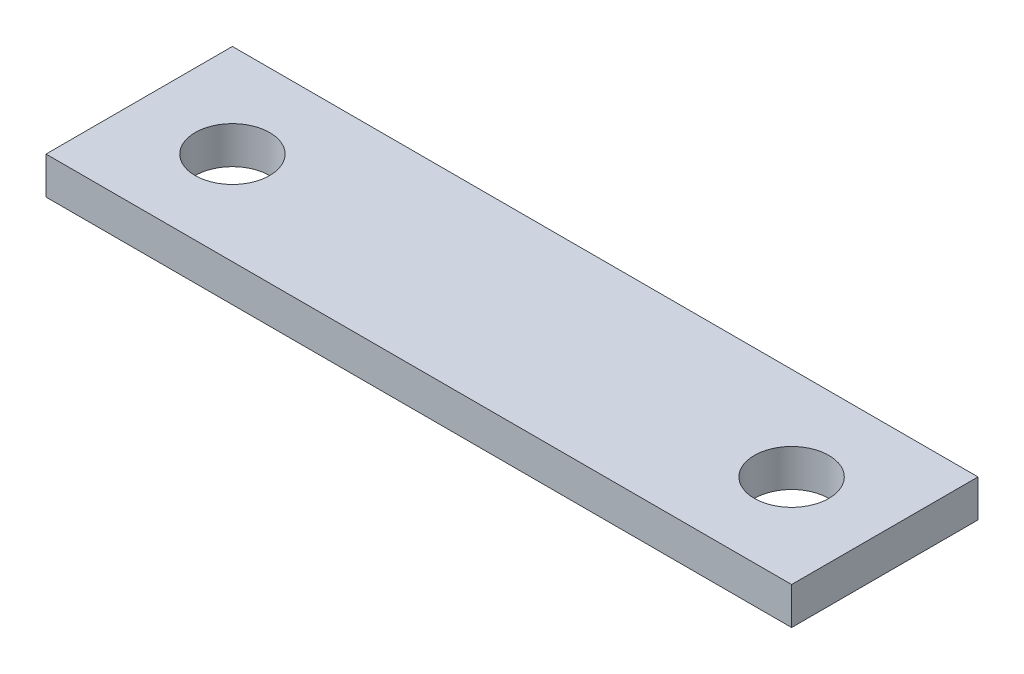
SolidWorks part; units mm, degrees
ref_plane "前视基准面" through (0, 0, 0) normal (0, 0, 1) x (1, 0, 0)
ref_plane "上视基准面" through (0, 0, 0) normal (0, 1, 0) x (1, 0, 0)
ref_plane "右视基准面" through (0, 0, 0) normal (1, 0, 0) x (0, 0, -1)
sketch "草图1" plane through (0, 0, 0) normal (0, 1, 0) x (1, 0, 0)
  line L0 (-1000, 15) -> (49000, 15) construction
  line L1 (0, 0) -> (120, 0)
  line L2 (0, 0) -> (0, 30)
  line L3 (0, 30) -> (120, 30)
  line L4 (120, 0) -> (120, 30)
  line L5 (60, -1000) -> (60, 49000) construction
  circle A0 centre (15, 15) radius 6
  circle A1 centre (105, 15) radius 6
  point P8 (0, 15)
  point P15 (60, 0)
  dimension "D3" = 12
  dimension "D4" = 12
  dimension "D1" = 120
  dimension "D2" = 30
  dimension "D5" = 90
extrude "凸台-拉伸1" add sketch "草图1" along normal blind 6
